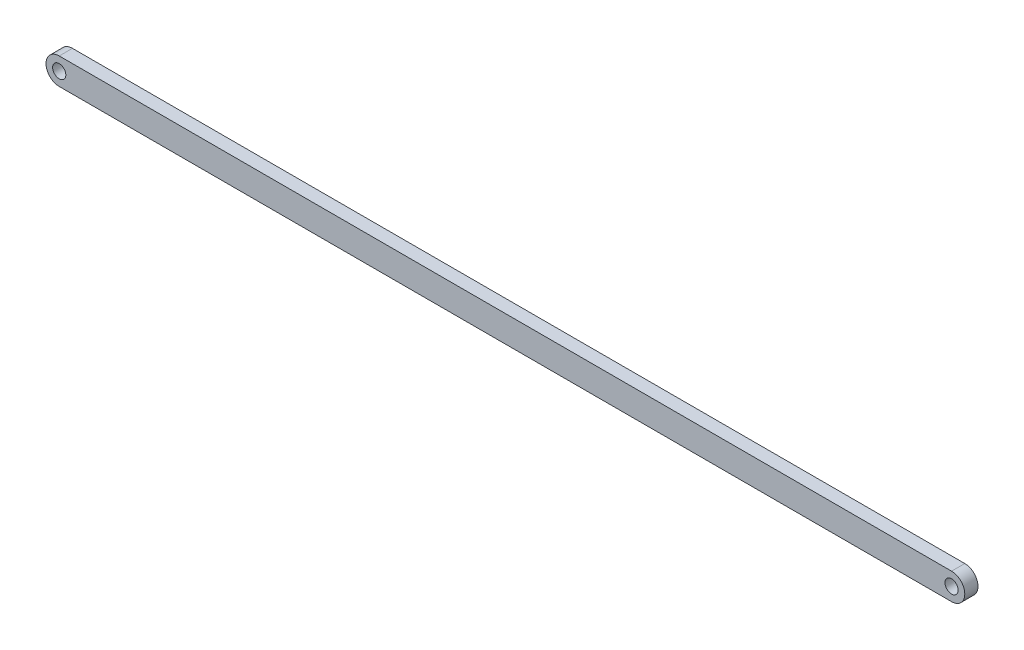
SolidWorks part; units mm, degrees
ref_plane "Plano frontal" through (0, 0, 0) normal (0, 0, 1) x (1, 0, 0)
ref_plane "Plano superior" through (0, 0, 0) normal (0, 1, 0) x (1, 0, 0)
ref_plane "Plano direito" through (0, 0, 0) normal (1, 0, 0) x (0, 0, -1)
sketch "Esboço1" plane through (0, 0, 0) normal (0, 0, 1) x (1, 0, 0)
  line L0 (-168.72, 5) -> (168.72, 5)
  line L1 (-168.72, 0) -> (168.72, 0) construction
  line L2 (-168.72, -5) -> (168.72, -5)
  arc A0 (-168.72, 5) -> (-168.72, -5) centre (-168.72, 0) ccw
  arc A1 (168.72, 5) -> (168.72, -5) centre (168.72, 0) cw
  circle A2 centre (-168.72, 0) radius 2.5
  circle A3 centre (168.72, 0) radius 2.5
  point P3 (0, 5)
  dimension "D1" = 337.44
  dimension "D2" = 10
extrude "Ressalto-extrusão1" add sketch "Esboço1" along normal blind 5
